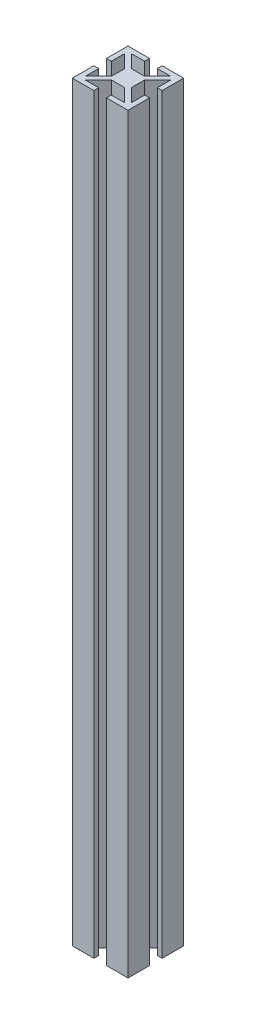
SolidWorks part; units mm, degrees
ref_plane "Front Plane" through (0, 0, 0) normal (0, 0, 1) x (1, 0, 0)
ref_plane "Top Plane" through (0, 0, 0) normal (0, 1, 0) x (1, 0, 0)
ref_plane "Right Plane" through (0, 0, 0) normal (1, 0, 0) x (0, 0, -1)
sketch "Sketch1" plane through (11.365, 0, 9.8462) normal (0, 1, 0) x (1, 0, 0)
  line L0 (-11.365, 9.8462) -> (-11.365, 32.3924) construction
  line L1 (-11.365, 9.8462) -> (-35.43, 9.8462) construction
  line L2 (-11.365, 9.8462) -> (-7.5972, 6.0784) construction
  line L3 (-24.065, 22.5462) -> (-14.2298, 22.5462)
  line L4 (-14.2298, 22.5462) -> (-14.2298, 20.3364)
  line L5 (-14.2298, 20.3364) -> (-20.2926, 20.3364)
  line L6 (-20.2926, 20.3364) -> (-14.3109, 14.3547)
  line L7 (-14.3109, 14.3547) -> (-8.4191, 14.3547)
  line L8 (-15.8735, 12.7921) -> (-15.8735, 6.9003)
  line L9 (-21.8552, 18.7738) -> (-15.8735, 12.7921)
  line L10 (-21.8552, 12.711) -> (-21.8552, 18.7738)
  line L11 (-24.065, 12.711) -> (-21.8552, 12.711)
  line L12 (-24.065, 22.5462) -> (-24.065, 12.711)
  line L13 (-14.3109, 5.3377) -> (-8.4191, 5.3377)
  line L14 (-20.2926, -0.644) -> (-14.3109, 5.3377)
  line L15 (-21.8552, 0.9186) -> (-15.8735, 6.9003)
  line L16 (-21.8552, 6.9814) -> (-21.8552, 0.9186)
  line L17 (-24.065, 6.9814) -> (-21.8552, 6.9814)
  line L18 (-24.065, -2.8538) -> (-24.065, 6.9814)
  line L19 (-14.2298, -0.644) -> (-20.2926, -0.644)
  line L20 (-14.2298, -2.8538) -> (-14.2298, -0.644)
  line L21 (-24.065, -2.8538) -> (-14.2298, -2.8538)
  line L22 (1.335, -2.8538) -> (-8.5002, -2.8538)
  line L23 (-8.5002, -2.8538) -> (-8.5002, -0.644)
  line L24 (-8.5002, -0.644) -> (-2.4374, -0.644)
  line L25 (1.335, -2.8538) -> (1.335, 6.9814)
  line L26 (1.335, 6.9814) -> (-0.8748, 6.9814)
  line L27 (-0.8748, 6.9814) -> (-0.8748, 0.9186)
  line L28 (-0.8748, 0.9186) -> (-6.8565, 6.9003)
  line L29 (-2.4374, -0.644) -> (-8.4191, 5.3377)
  line L30 (1.335, 22.5462) -> (1.335, 12.711)
  line L31 (1.335, 12.711) -> (-0.8748, 12.711)
  line L32 (-0.8748, 12.711) -> (-0.8748, 18.7738)
  line L33 (-0.8748, 18.7738) -> (-6.8565, 12.7921)
  line L34 (-6.8565, 12.7921) -> (-6.8565, 6.9003)
  line L35 (-2.4374, 20.3364) -> (-8.4191, 14.3547)
  line L36 (-8.5002, 20.3364) -> (-2.4374, 20.3364)
  line L37 (-8.5002, 22.5462) -> (-8.5002, 20.3364)
  line L38 (1.335, 22.5462) -> (-8.5002, 22.5462)
  point P20 (-15.8735, 9.8462)
  point P26 (-6.8565, 9.8462)
  point P36 (-11.365, 5.3377)
  point P42 (-11.365, 14.3547)
  dimension "D1" = 9.8352
  dimension "D2" = 12.7
  dimension "D3" = 4.5085
  dimension "D4" = 2.2098
  dimension "D5" = 1.1049
extrude "Boss-Extrude1" add sketch "Sketch1" along normal blind 342.9
other "1010<1>"
